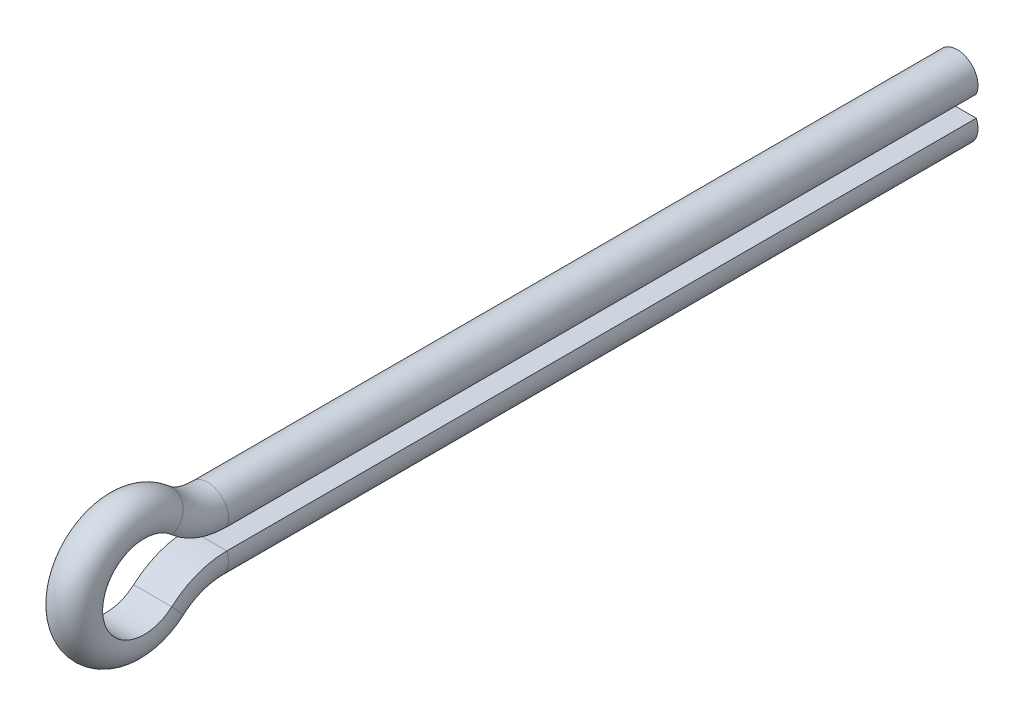
SolidWorks part; units mm, degrees
ref_plane "Front Plane" through (0, 0, 0) normal (0, 0, 1) x (1, 0, 0)
ref_plane "Top Plane" through (0, 0, 0) normal (0, 1, 0) x (1, 0, 0)
ref_plane "Right Plane" through (0, 0, 0) normal (1, 0, 0) x (0, 0, -1)
sketch "Sketch4" plane through (0, 0, 0) normal (0, 0, 1) x (1, 0, 0)
  line L0 (-2.2913, 0) -> (2.2913, 0)
  arc A0 (-2.2913, 0) -> (2.2913, 0) centre (0, -1) ccw
  point P3 (0, 0)
  dimension "D1" = 2.5
  dimension "D2" = 3.5
sketch "Sketch6" plane through (0, 0, 0) normal (1, 0, 0) x (0, 0, -1)
  line L0 (0, 2.5) -> (-90.0784, 2.5)
  line L3 (0, 0) -> (-90.0784, 0)
  arc A0 (-90.0784, 2.5) -> (-96.6928, 5) centre (-90.0784, 12.5) cw
  arc A1 (-96.6928, 5) -> (-96.6928, -2.5) centre (-100, 1.25) ccw
  arc A2 (-90.0784, 0) -> (-96.6928, -2.5) centre (-90.0784, -10) ccw
  dimension "D2" = 10
  dimension "D3" = 5
  dimension "D1" = 2.5
  dimension "D4" = 100
sweep "Sweep10" add profiles "Sketch4" path "Sketch6"
